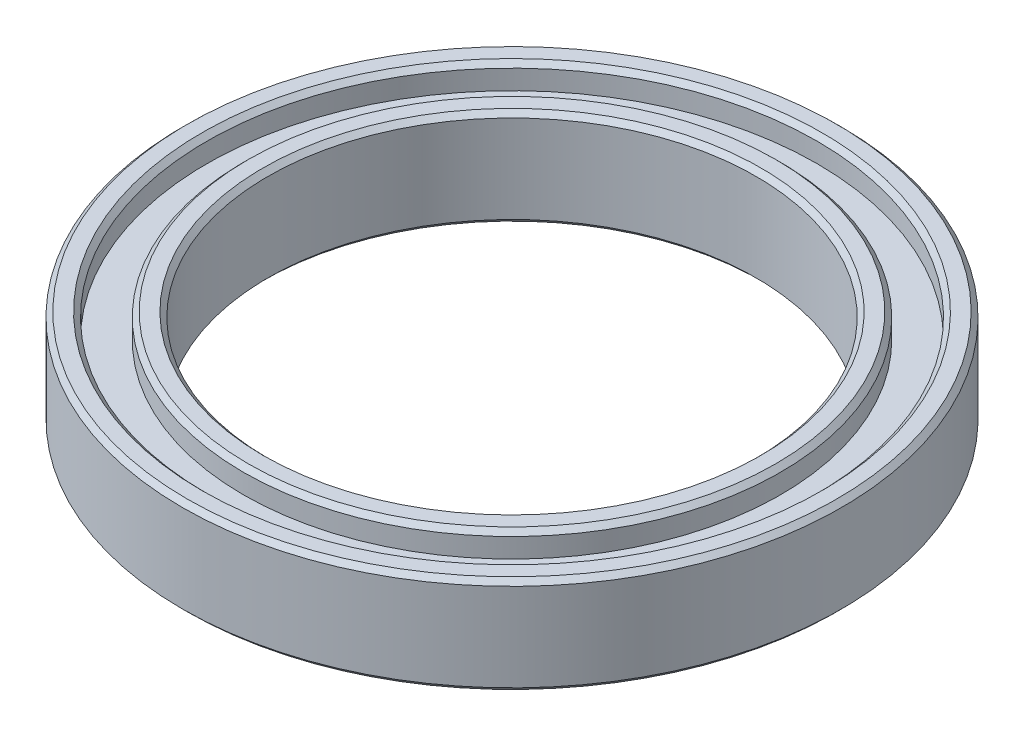
SolidWorks part; units mm, degrees
ref_plane "Front Plane" through (0, 0, 0) normal (0, 0, 1) x (1, 0, 0)
ref_plane "Top Plane" through (0, 0, 0) normal (0, 1, 0) x (1, 0, 0)
ref_plane "Right Plane" through (0, 0, 0) normal (1, 0, 0) x (0, 0, -1)
sketch "Sketch1" plane through (0, 0, 0) normal (0, 1, 0) x (1, 0, 0)
  circle A0 centre (0, 0) radius 13.5
  circle A1 centre (0, 0) radius 10
  dimension "D1" = 27
  dimension "D2" = 20
extrude "Boss-Extrude1" add sketch "Sketch1" along normal blind 4
sketch "Sketch2" plane through (0, 4, 0) normal (0, 1, 0) x (1, 0, 0)
  circle A0 centre (0, 0) radius 11
  circle A1 centre (0, 0) radius 12.5
  dimension "D1" = 25
  dimension "D2" = 22
extrude "Cut-Extrude1" cut sketch "Sketch2" against normal blind 1
sketch "Sketch3" plane through (0, 0, 0) normal (0, -1, 0) x (1, 0, 0)
  circle A0 centre (0, 0) radius 11
  circle A1 centre (0, 0) radius 12.5
  dimension "D1" = 25
  dimension "D2" = 22
extrude "Cut-Extrude2" cut sketch "Sketch3" against normal blind 1
chamfer "Chamfer1" distance 0.2 angle 45 8 edges at (0, 4, 11) (0, 4, 10) (0, 4, 13.5) (0, 4, 12.5) (0, 0, 13.5) (0, 0, -12.5) (0, 0, -11) (0, 0, 10)
